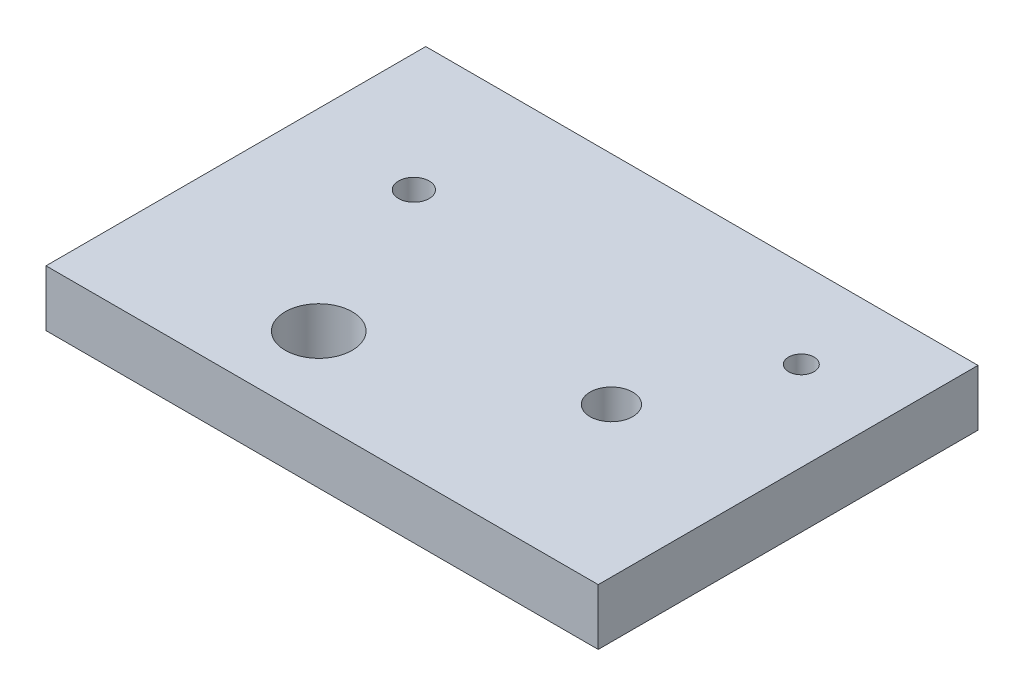
SolidWorks part; units mm, degrees
ref_plane "Front Plane" through (0, 0, 0) normal (0, 0, 1) x (1, 0, 0)
ref_plane "Top Plane" through (0, 0, 0) normal (0, 1, 0) x (1, 0, 0)
ref_plane "Right Plane" through (0, 0, 0) normal (1, 0, 0) x (0, 0, -1)
sketch "Sketch1" plane through (0, 0, 0) normal (0, 1, 0) x (1, 0, 0)
  line L1 (-42.7767, -28.9733) -> (55.566, -28.9733)
  line L2 (-42.7767, -28.9733) -> (-42.7767, 38.6562)
  line L3 (-42.7767, 38.6562) -> (55.566, 38.6562)
  line L4 (55.566, -28.9733) -> (55.566, 38.6562)
  circle A0 centre (39.6799, 23.0727) radius 2.2694
  circle A1 centre (28.9378, 0) radius 3.7983
  circle A2 centre (-8.4324, -14.7514) radius 5.9623
  circle A3 centre (-21.7465, 15.5079) radius 2.7233
extrude "Boss-Extrude1" add sketch "Sketch1" along normal blind 10
